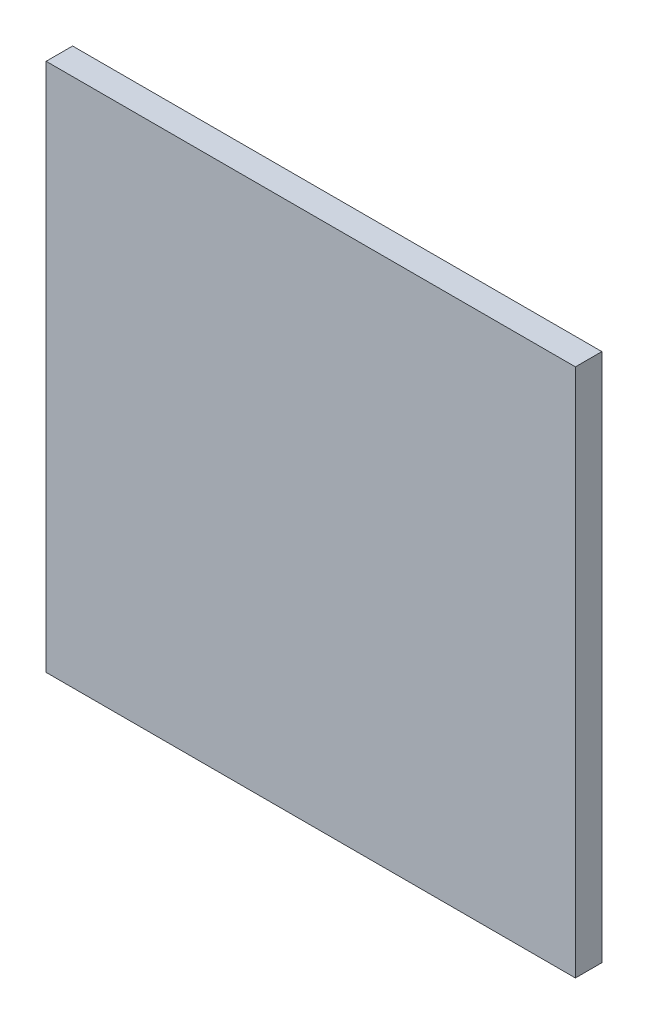
SolidWorks part; units mm, degrees
ref_plane "Front Plane" through (0, 0, 0) normal (0, 0, 1) x (1, 0, 0)
ref_plane "Top Plane" through (0, 0, 0) normal (0, 1, 0) x (1, 0, 0)
ref_plane "Right Plane" through (0, 0, 0) normal (1, 0, 0) x (0, 0, -1)
sketch "Sketch1" plane through (0, 0, 0) normal (0, 0, 1) x (1, 0, 0)
  line L1 (0, 25.3083) -> (50.8, 25.3083)
  line L2 (0, 25.3083) -> (0, 76.1083)
  line L3 (0, 76.1083) -> (50.8, 76.1083)
  line L4 (50.8, 25.3083) -> (50.8, 76.1083)
  dimension "D1" = 50.8
  dimension "D2" = 50.8
extrude "Boss-Extrude1" add sketch "Sketch1" along normal blind 2.54
